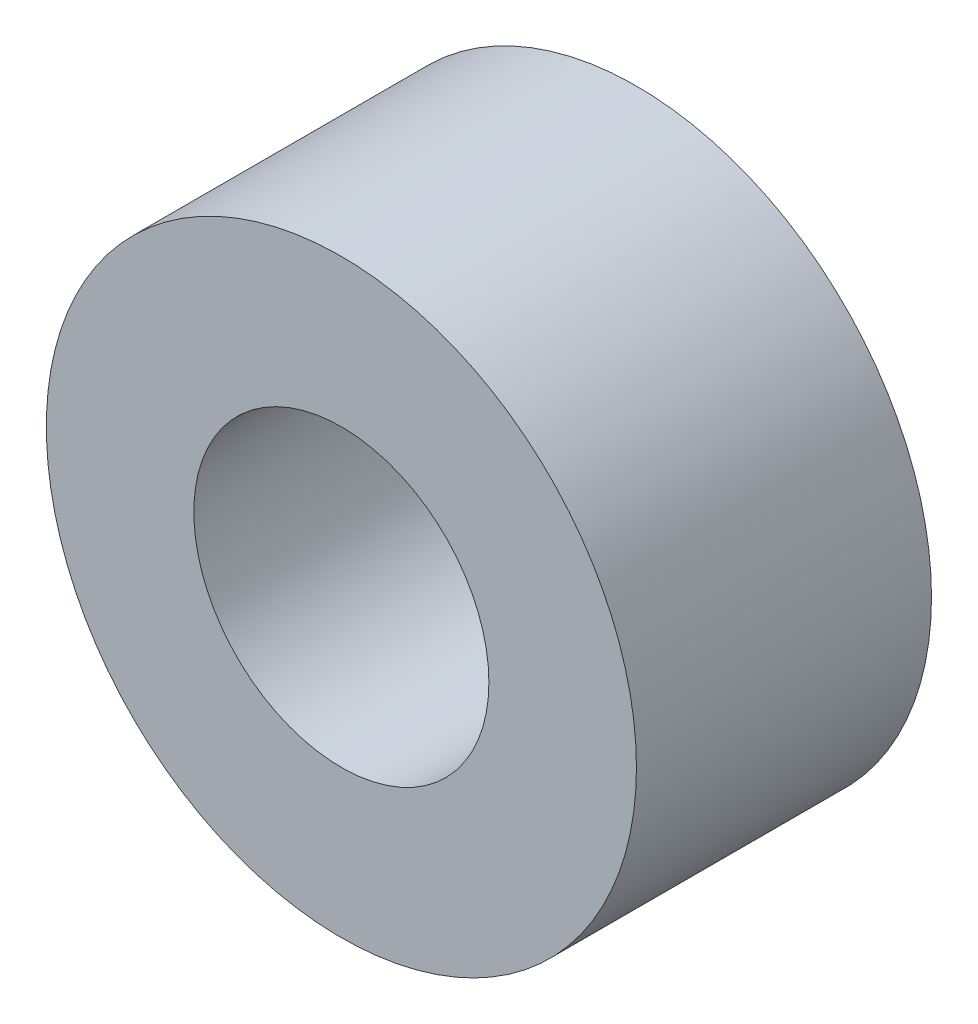
SolidWorks part; units mm, degrees
ref_plane "Plan de face" through (0, 0, 0) normal (0, 0, 1) x (1, 0, 0)
ref_plane "Plan de dessus" through (0, 0, 0) normal (0, 1, 0) x (1, 0, 0)
ref_plane "Plan de droite" through (0, 0, 0) normal (1, 0, 0) x (0, 0, -1)
sketch "Esquisse1" plane through (0, 0, 0) normal (0, 0, 1) x (1, 0, 0)
  circle A0 centre (0, 0) radius 3.175
  circle A1 centre (0, 0) radius 6.35
  dimension "D1" = 6.35
  dimension "D2" = 12.7
extrude "Boss.-Extru.1" add sketch "Esquisse1" along normal blind 6.35
